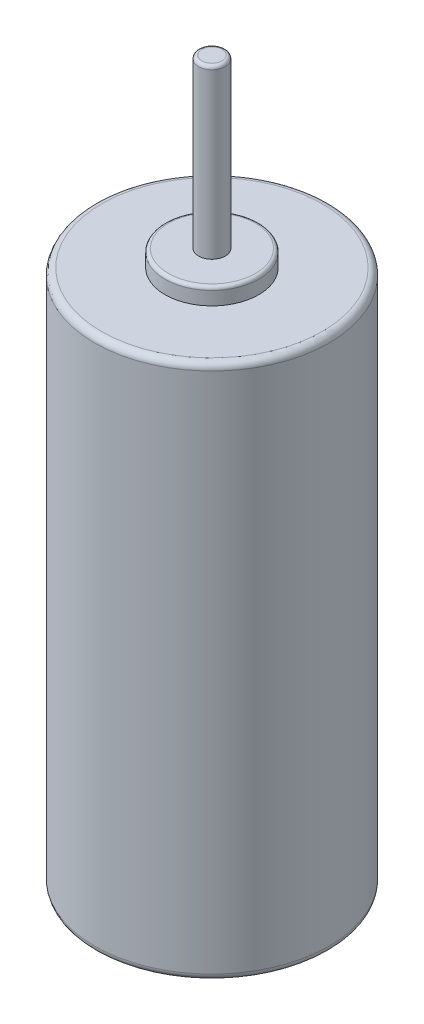
SolidWorks part; units mm, degrees
ref_plane "Front" through (0, 0, 0) normal (0, 0, 1) x (1, 0, 0)
ref_plane "Top" through (0, 0, 0) normal (0, 1, 0) x (1, 0, 0)
ref_plane "Right" through (0, 0, 0) normal (1, 0, 0) x (0, 0, -1)
sketch "Sketch1" plane through (0, 0, 0) normal (0, 1, 0) x (1, 0, 0)
  circle A0 centre (0, 0) radius 3.5
extrude "Boss-Extrude1" add sketch "Sketch1" along normal blind 16 contours A0
sketch "Sketch4" plane through (0, 16, 0) normal (0, 1, 0) x (1, 0, 0)
  circle A0 centre (0, 0) radius 1.4
  point P0 (0, 0)
extrude "Boss-Extrude2" add sketch "Sketch4" along normal blind 0.5 contours A0
sketch "Sketch5" plane through (0, 16.5, 0) normal (0, 1, 0) x (1, 0, 0)
  circle A0 centre (0, 0) radius 0.4
  point P0 (0, 0)
extrude "Boss-Extrude3" add sketch "Sketch5" along normal blind 5 contours A0
fillet "Fillet1" radius 0.1 1 edges at (0, 21.5, 0.4)
fillet "Fillet2" radius 0.2 1 edges at (0, 16, 3.5)
fillet "Fillet3" radius 0.2 1 edges at (0, 0, 3.5)
fillet "Fillet4" radius 0.1 1 edges at (0, 16.5, 1.4)
